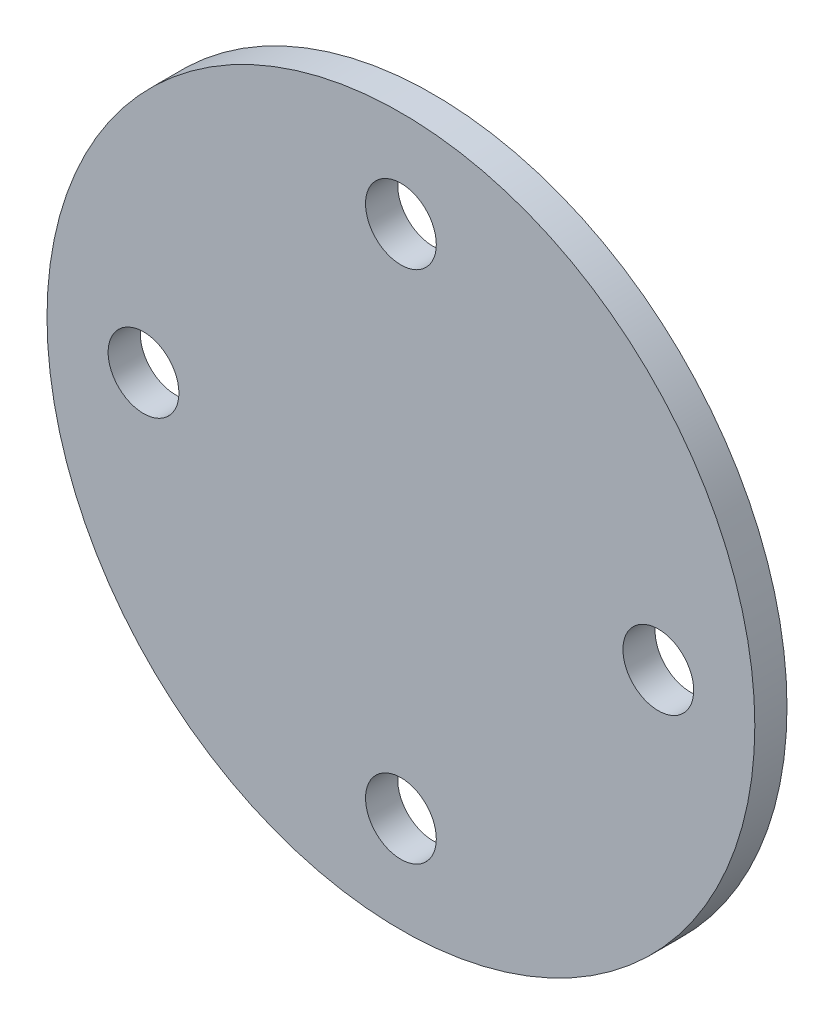
SolidWorks part; units mm, degrees
ref_plane "Alzado" through (0, 0, 0) normal (0, 0, 1) x (1, 0, 0)
ref_plane "Planta" through (0, 0, 0) normal (0, 1, 0) x (1, 0, 0)
ref_plane "Vista lateral" through (0, 0, 0) normal (1, 0, 0) x (0, 0, -1)
sketch "Croquis2" plane through (0, 0, 0) normal (0, 0, 1) x (1, 0, 0)
  line L0 (0, 0) -> (0, 8) construction
  circle A0 centre (0, 0) radius 11
  circle A1 centre (0, 8) radius 1.1
  circle A2 centre (8, 0) radius 1.1
  circle A3 centre (0, -8) radius 1.1
  circle A4 centre (-8, 0) radius 1.1
  point P14 (0, 0)
  dimension "D1" = 22
  dimension "D4" = 2.2
  dimension "D3" = 8
  dimension "D2" = 4
extrude "Saliente-Extruir1" add sketch "Croquis2" along normal blind 1
